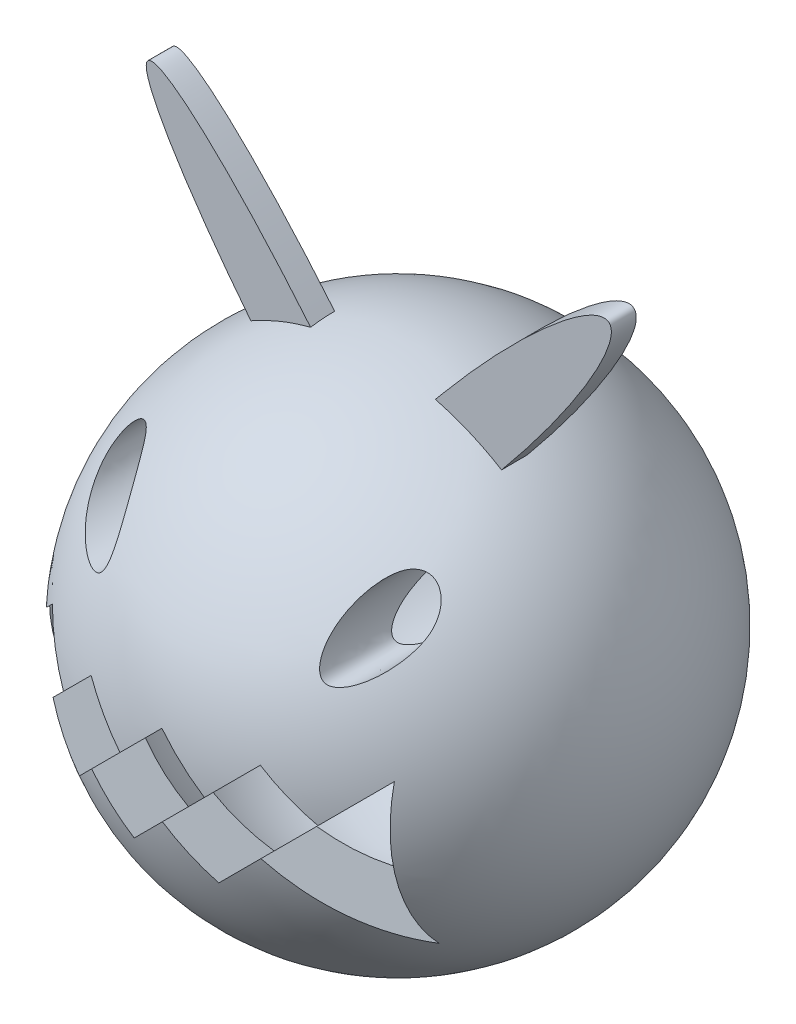
SolidWorks part; units mm, degrees
ref_plane "Front Plane" through (0, 0, 0) normal (0, 0, 1) x (1, 0, 0)
ref_plane "Top Plane" through (0, 0, 0) normal (0, 1, 0) x (1, 0, 0)
ref_plane "Right Plane" through (0, 0, 0) normal (1, 0, 0) x (0, 0, -1)
sketch "Sketch4" plane through (0, 0, 0) normal (0, 0, 1) x (1, 0, 0)
  line L0 (0, 48.4906) -> (0, -51.5094) construction
  arc A0 (0, 48.4906) -> (0, -51.5094) centre (0, -1.5094) cw
  dimension "D1" = 100
revolve "Revolve-Thin1" add sketch "Sketch4" angle 360 about L0
sketch "Sketch5" plane through (0, 0, 0) normal (0, 0, 1) x (1, 0, 0)
  line L0 (-30.644, -9.9701) -> (-40.0332, -26.2723)
  line L1 (-40.0332, -26.2723) -> (-40.0332, 6.3321)
  line L2 (-30.644, -9.9701) -> (-22.4929, -18.1212)
  line L3 (-22.4929, -18.1212) -> (-14.3418, -9.9701)
  line L4 (-14.3418, -9.9701) -> (-6.1907, -18.1212)
  line L5 (-6.1907, -18.1212) -> (1.9604, -9.9701)
  line L6 (1.9604, -9.9701) -> (10.1115, -18.1212)
  line L7 (10.1115, -18.1212) -> (18.2626, -9.9701)
  line L8 (18.2626, -9.9701) -> (26.4137, -18.1212)
  line L9 (26.4137, -18.1212) -> (34.5648, -26.2723)
  line L10 (34.5648, -9.9701) -> (34.5648, 6.3321)
  line L11 (34.5648, 6.3321) -> (26.4137, -1.819)
  line L12 (26.4137, -1.819) -> (18.2626, 6.3321)
  line L13 (18.2626, 6.3321) -> (10.1115, -1.819)
  line L14 (10.1115, -1.819) -> (1.9604, 6.3321)
  line L15 (1.9604, 6.3321) -> (-6.1907, -1.819)
  line L16 (-6.1907, -1.819) -> (-14.3418, 6.3321)
  line L17 (-14.3418, 6.3321) -> (-22.4929, -1.819)
  line L18 (-22.4929, -1.819) -> (-30.644, 6.3321)
  line L19 (-30.644, 6.3321) -> (-36.9761, 0)
  line L20 (-36.9761, 0) -> (-40.0332, 6.3321)
  line L21 (34.5648, -26.2723) -> (34.5648, -9.9701)
  point P3 (-40.0332, 12.626)
  point P22 (-22.4929, -1.819)
  point P26 (-30.644, -9.9701)
extrude "Cut-Extrude1" cut sketch "Sketch5" along normal blind 50
sketch "Sketch6" plane through (0, 0, 0) normal (0, 0, 1) x (1, 0, 0)
  spline S0 degree 3 poles (-22.4028, 39.8795) (-36.9407, 23.6934) (-10.6097, 12.4405) (-22.4028, 39.8795) (-36.9407, 23.6934) (-10.6097, 12.4405) knots -1 -0.629243 -0.242259 0 0.370757 0.757741 1 1.370757 1.757741 2 only from (-31.1599, 26.2456) to (-31.1599, 26.2456)
  spline S1 degree 3 poles (23.0548, 40.0614) (19.3674, 13.1527) (37.0509, 25.4882) (23.0548, 40.0614) (19.3674, 13.1527) (37.0509, 25.4882) knots -1 -0.687642 -0.406844 0 0.312358 0.593156 1 1.312358 1.593156 2 only from (23.9374, 19.6421) to (23.9374, 19.6421)
extrude "Cut-Extrude2" cut sketch "Sketch6" along normal blind 50
sketch "Sketch8" plane through (0, 0, 0) normal (0, 0, 1) x (1, 0, 0)
  line L0 (-21.1784, 37.6282) -> (-11.5697, 45.4822)
  ellipse E0 centre (-16.374, 41.5552) end of major axis (-45.1263, 76.7314) minor radius 6.2051 (-11.5697, 45.4822) -> (-21.1784, 37.6282) ccw
extrude "Boss-Extrude1" add sketch "Sketch8" along normal blind 5
sketch "Sketch9" plane through (0, 0, 0) normal (0, 0, 1) x (1, 0, 0)
  line L1 (14.4164, 48.8762) -> (6.9873, 40.0137)
  line L2 (6.9873, 40.0137) -> (17.5599, 31.1511)
  line L3 (17.5599, 31.1511) -> (24.989, 40.0137)
  arc A0 (-24.6737, 41.9786) -> (-12.6954, 46.852) centre (0, -1.5094) ccw construction
  ellipse E0 centre (19.7027, 44.4449) end of major axis (47.3593, 77.438) minor radius 6.8979 (24.989, 40.0137) -> (14.4164, 48.8762) ccw
extrude "Boss-Extrude2" add sketch "Sketch9" along normal blind 5
